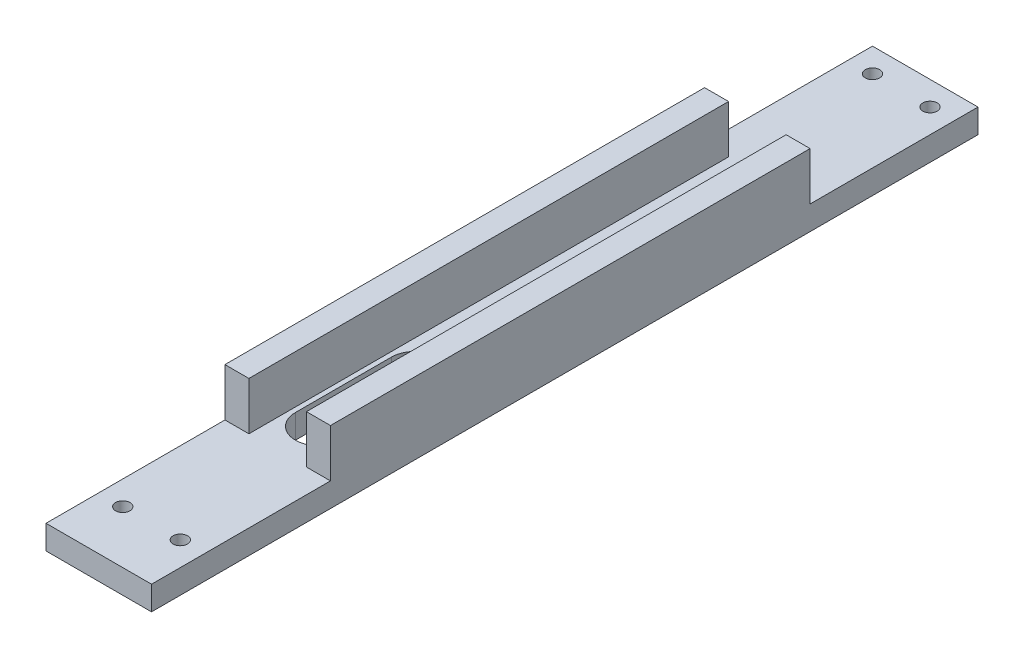
SolidWorks part; units mm, degrees
ref_plane "Front" through (0, 0, 0) normal (0, 0, 1) x (1, 0, 0)
ref_plane "Top" through (0, 0, 0) normal (0, 1, 0) x (1, 0, 0)
ref_plane "Right" through (0, 0, 0) normal (1, 0, 0) x (0, 0, -1)
sketch "Sketch1" plane through (0, 0, 0) normal (0, 1, 0) x (1, 0, 0)
  line L0 (11, 166.3) -> (11, 161.3)
  line L1 (0, 0) -> (22, 0)
  line L2 (0, 0) -> (0, 166.3)
  line L3 (0, 166.3) -> (22, 166.3)
  line L4 (22, 0) -> (22, 166.3)
  line L5 (5, 161.3) -> (17, 161.3)
  line L6 (0, 83.15) -> (22, 83.15)
  circle A0 centre (5, 161.3) radius 1.5
  circle A1 centre (17, 161.3) radius 1.5
  circle A2 centre (17, 5) radius 1.5
  circle A3 centre (5, 5) radius 1.5
  point P10 (11, 161.3)
  dimension "D1" = 166.3
  dimension "D2" = 22
  dimension "D3" = 12
extrude "Boss-Extrude1" add sketch "Sketch1" along normal blind 5
sketch "Sketch2" plane through (0, 0, 0) normal (0, -1, 0) x (-1, 0, 0)
  line L0 (-11, 0) -> (-11, 40)
  line L1 (0, 0) -> (-22, 0) construction
  line L2 (-11, 40) -> (-11, 60)
  line L3 (-11, 40) -> (-11, 60) construction
  line L4 (-16, 40) -> (-16, 60)
  line L5 (-6, 40) -> (-6, 60)
  arc A0 (-16, 40) -> (-6, 40) centre (-11, 40) ccw
  arc A1 (-6, 60) -> (-16, 60) centre (-11, 60) ccw
  point P5 (-11, 50)
  dimension "D3" = 5
  dimension "D1" = 40
  dimension "D2" = 20
extrude "Cut-Extrude1" cut sketch "Sketch2" against normal blind 5
sketch "Sketch3" plane through (0, 0, 0) normal (0, 0, 1) x (1, 0, 0)
  line L1 (22, 0) -> (0, 0)
  line L2 (22, 0) -> (22, 5)
  line L3 (22, 5) -> (0, 5)
  line L4 (0, 0) -> (0, 5)
extrude "Boss-Extrude2" add sketch "Sketch3" along normal blind 6
sketch "Sketch4" plane through (0, 5, 0) normal (0, 1, 0) x (1, 0, 0)
  line L0 (0, -6) -> (0, 166.3) construction
  line L1 (0, 131.3) -> (5, 131.3)
  line L2 (0, 131.3) -> (0, 31.3)
  line L3 (0, 31.3) -> (5, 31.3)
  line L4 (5, 131.3) -> (5, 31.3)
  line L5 (0, 166.3) -> (22, 166.3) construction
  line L6 (11, 166.3) -> (11, 159.0709)
  line L7 (22, 31.3) -> (17, 31.3)
  line L8 (17, 131.3) -> (17, 31.3)
  line L9 (22, 131.3) -> (17, 131.3)
  line L10 (22, 131.3) -> (22, 31.3)
  line M14 (0, 166.3) -> (0, -6)
  dimension "D1" = 35
  dimension "D2" = 100
  dimension "D3" = 5
extrude "Boss-Extrude3" add sketch "Sketch4" along normal blind 10 contours L4 L1 L3 M14 | L10 L7 L8 L9
